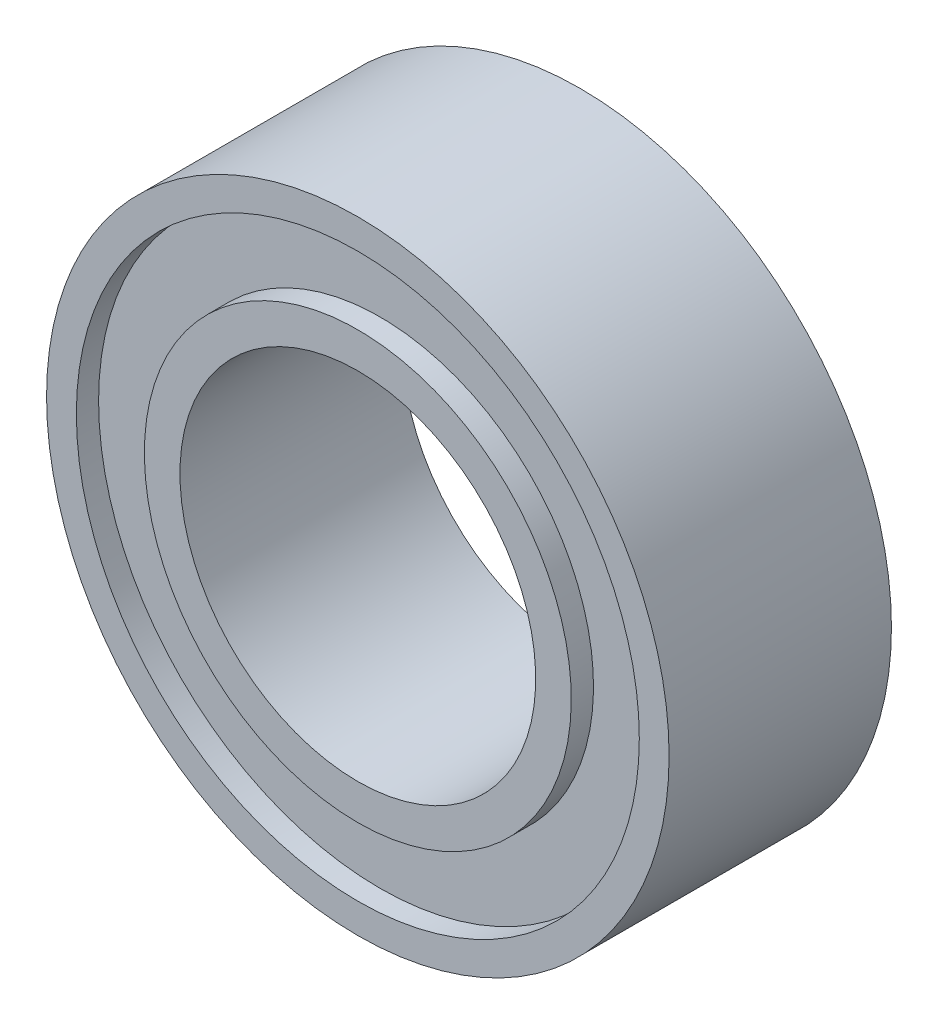
SolidWorks part; units mm, degrees
ref_plane "Front Plane" through (0, 0, 0) normal (0, 0, 1) x (1, 0, 0)
ref_plane "Top Plane" through (0, 0, 0) normal (0, 1, 0) x (1, 0, 0)
ref_plane "Right Plane" through (0, 0, 0) normal (1, 0, 0) x (0, 0, -1)
sketch "Sketch1" plane through (0, 0, 0) normal (1, 0, 0) x (0, 0, -1)
  line L0 (-1.25, 0) -> (1.25, 0) construction
  line L1 (-1.25, 3.5) -> (-1.25, 0) construction
  line L2 (-1.25, 3.5) -> (1.25, 3.5)
  line L3 (-1.25, 3.5) -> (-1.25, 3.165)
  line L4 (-1.25, 3.165) -> (-1, 3.165)
  line L5 (1.25, 3.5) -> (1.25, 3.165)
  line L6 (-1.25, 2.4) -> (-1, 2.4)
  line L7 (-1.25, 2.4) -> (-1.25, 2)
  line L8 (-1.25, 2) -> (1.25, 2)
  line L9 (1.25, 2.4) -> (1.25, 2)
  line L10 (1.25, 3.5) -> (1.25, 0) construction
  line L11 (-1, 3.165) -> (-1, 2.4)
  line L12 (0, 3.5) -> (0, 0) construction
  line L13 (1, 3.165) -> (1, 2.4)
  line L14 (1, 3.165) -> (1.25, 3.165)
  line L15 (1, 2.4) -> (1.25, 2.4)
  point P3 (0, 0)
  dimension "D1" = 4
  dimension "D2" = 7
  dimension "D3" = 4.8
  dimension "D4" = 2.5
  dimension "D6" = 6.33
  dimension "D7" = 1
revolve "Revolve1" add sketch "Sketch1" angle 360 about L0
fillet "Fillet1" [suppressed] radius 0.15
fillet "Fillet2" [suppressed] radius 0.15
